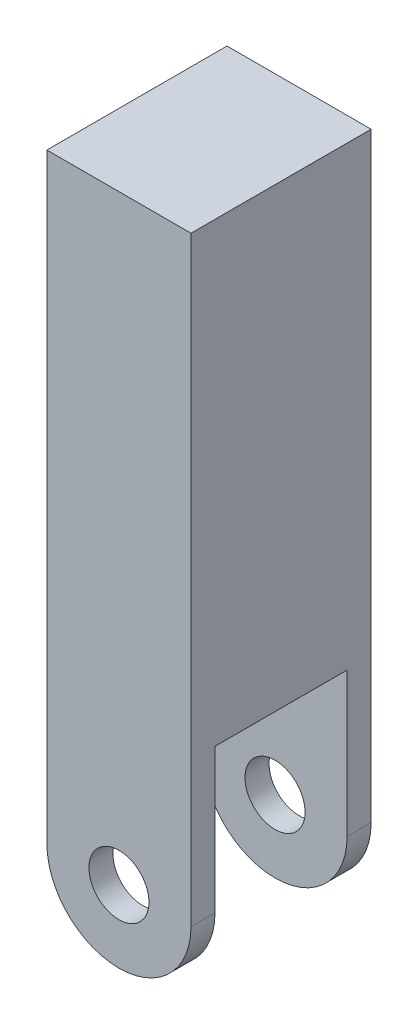
SolidWorks part; units mm, degrees
ref_plane "Front Plane" through (0, 0, 0) normal (0, 0, 1) x (1, 0, 0)
ref_plane "Top Plane" through (0, 0, 0) normal (0, 1, 0) x (1, 0, 0)
ref_plane "Right Plane" through (0, 0, 0) normal (1, 0, 0) x (0, 0, -1)
sketch "Sketch1" plane through (0, 0, 0) normal (0, 0, 1) x (1, 0, 0)
  line L0 (-6, 0) -> (-6, 50)
  line L1 (-6, 50) -> (6, 50)
  line L2 (6, 50) -> (6, 0)
  circle A0 centre (0, 0) radius 2.5
  arc A1 (-6, 0) -> (6, 0) centre (0, 0) ccw
  dimension "D1" = 50
extrude "Boss-Extrude2" add sketch "Sketch1" along normal mid plane 15
sketch "Sketch2" plane through (0, 0, 0) normal (1, 0, 0) x (0, 0, -1)
  line L0 (-7.5, 50) -> (7.5, 50) construction
  line L1 (-5.5, 12) -> (5.5, 12)
  line L2 (-5.5, 12) -> (-5.5, -22.5011)
  line L3 (-5.5, -22.5011) -> (5.5, -22.5011)
  line L4 (5.5, 12) -> (5.5, -22.5011)
  line L5 (-5.5, 12) -> (5.5, -22.5011) construction
  line L6 (-5.5, -22.5011) -> (5.5, 12) construction
  point P0 (0, -5.2506)
  point P5 (0, 0)
  dimension "D1" = 11
  dimension "D2" = 38
extrude "Cut-Extrude1" cut sketch "Sketch2" against normal through all both and the other way through all
